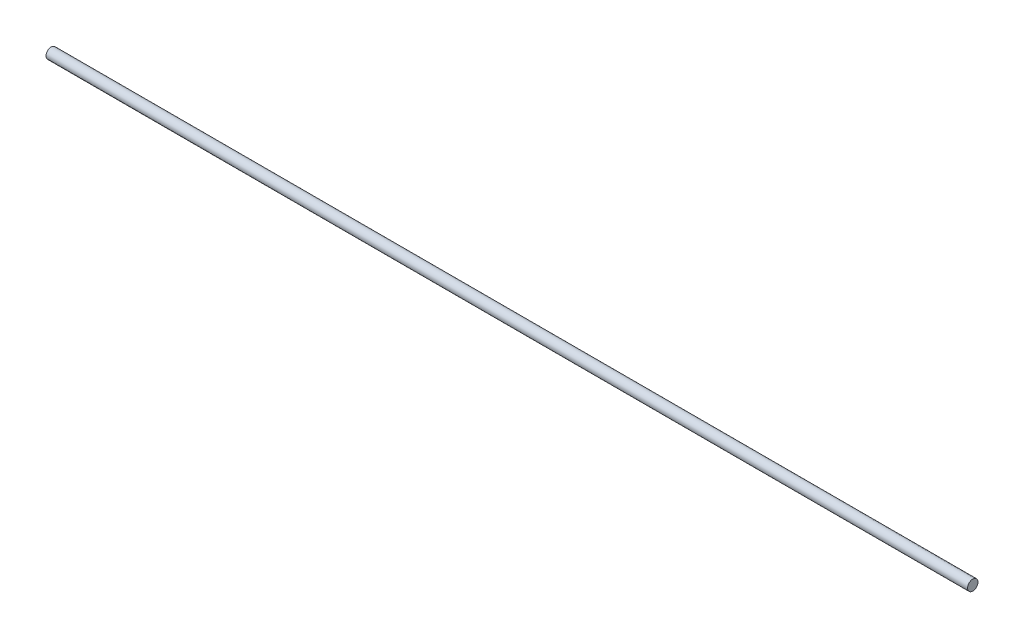
SolidWorks part; units mm, degrees
material "6061-T6 (SS)"
ref_plane "Front Plane" through (0, 0, 0) normal (1, 0, 0) x (0, 1, 0)
ref_plane "Top Plane" through (0, 0, 0) normal (0, 0, 1) x (0, 1, 0)
ref_plane "Right Plane" through (0, 0, 0) normal (0, 1, 0) x (-1, 0, 0)
sketch "Sketch1" plane through (0, 0, 0) normal (1, 0, 0) x (0, 1, 0)
  circle A0 centre (0, 0) radius 6.35
  dimension "D1" = 12.7
extrude "Boss-Extrude1" add sketch "Sketch1" along normal blind 1122.172
equation "\"D\"= 0.60in"
equation "\"E\"= 10000000"
equation "\"F\" = 450"
equation "\"def\"= 0.009"
equation "\"A\"= PI * \"D\" ^ 2 / 4"
equation "\"L\"= \"def\" * \"A\" * \"E\" / \"F\""
equation "\"rho\"= 0.0975"
equation "\"W\"= \"rho\" * \"A\" * \"L\""
